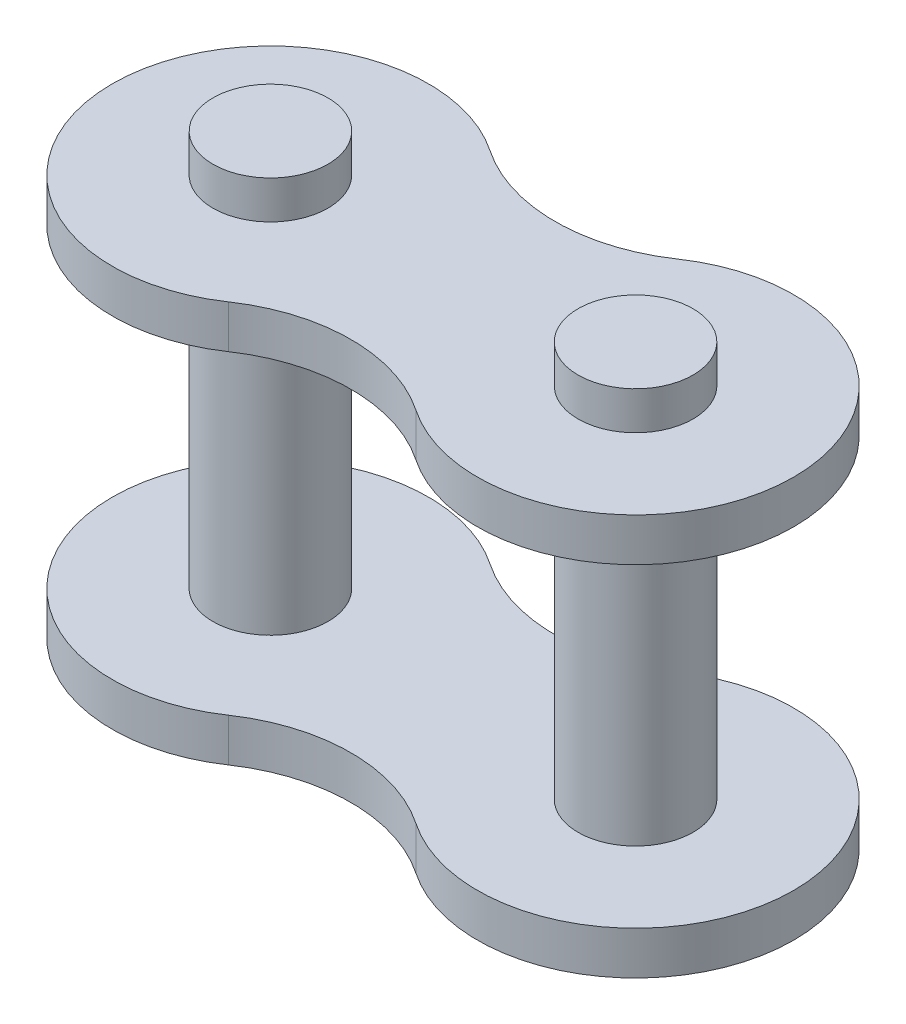
SolidWorks part; units mm, degrees
material "Aço carbono simples"
ref_plane "Plano frontal" through (0, 0, 0) normal (0, 0, 1) x (1, 0, 0)
ref_plane "Plano superior" through (0, 0, 0) normal (0, 1, 0) x (1, 0, 0)
ref_plane "Plano direito" through (0, 0, 0) normal (1, 0, 0) x (0, 0, -1)
ref_plane "Plano2" through (0, 6.975, 0) normal (0, 1, 0) x (1, 0, 0)
sketch "Esboço5" plane through (0, 6.975, 0) normal (0, 1, 0) x (1, 0, 0)
  circle A0 centre (6.35, 0) radius 2
  circle A1 centre (-6.35, 0) radius 2
  arc A2 (3.2631, 4.5521) -> (-3.2631, 4.5521) centre (0, 9.3641) cw
  arc A3 (-3.2631, 4.5521) -> (-3.2631, -4.5521) centre (-6.35, 0) ccw
  arc A4 (-3.2631, -4.5521) -> (3.2631, -4.5521) centre (0, -9.3641) cw
  arc A5 (3.2631, -4.5521) -> (3.2631, 4.5521) centre (6.35, 0) ccw
extrude "Ressalto-extrusão1" add sketch "Esboço5" against normal blind 1.5 separate body
ref_plane "Plano3" through (0, -6.975, 0) normal (0, -1, 0) x (-1, 0, 0)
sketch "Esboço10" plane through (0, -6.975, 0) normal (0, -1, 0) x (-1, 0, 0)
  circle A0 centre (-6.35, 0) radius 2
  circle A1 centre (6.35, 0) radius 2
  arc A2 (3.2631, 4.5521) -> (-3.2631, 4.5521) centre (0, 9.3641) cw
  arc A3 (-3.2631, 4.5521) -> (-3.2631, -4.5521) centre (-6.35, 0) ccw
  arc A4 (-3.2631, -4.5521) -> (3.2631, -4.5521) centre (0, -9.3641) cw
  arc A5 (3.2631, -4.5521) -> (3.2631, 4.5521) centre (6.35, 0) ccw
extrude "Ressalto-extrusão2" add sketch "Esboço10" against normal blind 1.5 separate body
ref_plane "Plano4" through (0, 0, 0) normal (0, 0, -1) x (-1, 0, 0)
sketch "Esboço16" plane through (0, 0, 0) normal (0, 0, -1) x (-1, 0, 0)
  line L0 (4.35, -8.3) -> (6.35, -8.3)
  line L1 (6.35, -8.3) -> (6.35, 8.3)
  line L2 (6.35, 8.3) -> (4.35, 8.3)
  line L3 (4.35, 8.3) -> (4.35, -8.3)
  line L4 (6.35, -8.3) -> (6.35, 8.3) construction
revolve "Revolução2" add sketch "Esboço16" angle 360 about L1
sketch "Esboço23" plane through (0, 0, 0) normal (0, 0, -1) x (-1, 0, 0)
  line L0 (-8.35, -8.3) -> (-6.35, -8.3)
  line L1 (-6.35, -8.3) -> (-6.35, 8.3)
  line L2 (-6.35, 8.3) -> (-8.35, 8.3)
  line L3 (-8.35, 8.3) -> (-8.35, -8.3)
  line L4 (-6.35, -8.3) -> (-6.35, 8.3) construction
revolve "Revolução3" add sketch "Esboço23" angle 360 about L1
